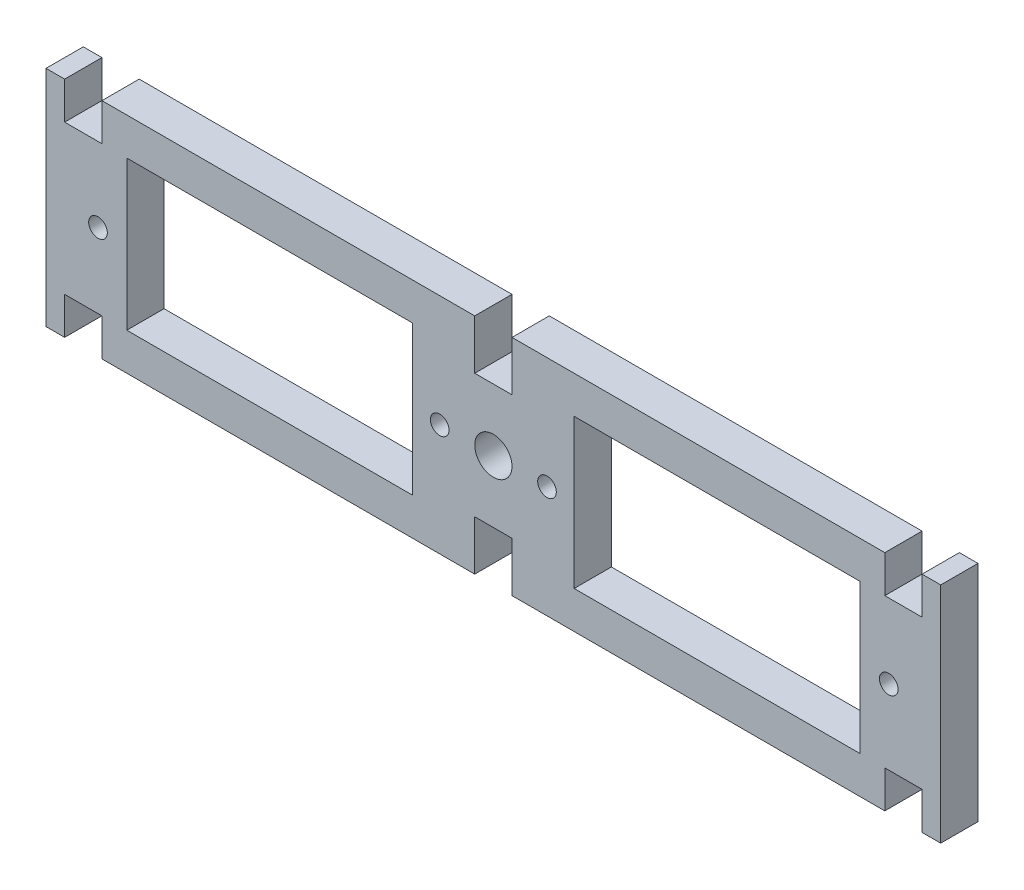
SolidWorks part; units mm, degrees
ref_plane "前视基准面" through (0, 0, 0) normal (0, 0, 1) x (1, 0, 0)
ref_plane "上视基准面" through (0, 0, 0) normal (0, 1, 0) x (1, 0, 0)
ref_plane "右视基准面" through (0, 0, 0) normal (1, 0, 0) x (0, 0, -1)
other "Configuration Table"
sketch "草图1" plane through (0, 0, 0) normal (0, 0, 1) x (1, 0, 0)
  line L0 (0, 0) -> (0, -18)
  line L1 (0, -18) -> (1.5, -18)
  line L2 (1.5, -18) -> (1.5, -15)
  line L3 (1.5, -15) -> (4.5, -15)
  line L4 (4.5, -15) -> (4.5, -18)
  line L5 (4.5, -18) -> (34.5, -18)
  line L6 (34.5, -18) -> (34.5, -14)
  line L7 (34.5, -14) -> (37.5, -14)
  line L8 (0, 0) -> (1.5, 0)
  line L9 (1.5, 0) -> (1.5, -3)
  line L10 (1.5, -3) -> (4.5, -3)
  line L11 (4.5, -3) -> (4.5, 0)
  line L12 (4.5, 0) -> (34.5, 0)
  line L13 (34.5, 0) -> (34.5, -4)
  line L14 (34.5, -4) -> (37.5, -4)
  line L15 (36, 6.2675) -> (36, -27.0405) construction
  line L16 (29.5, -9) -> (29.5, -15)
  line L17 (42.5, -24.4938) -> (29.5, -24.4938) construction
  line L18 (29.5, -15) -> (6.5, -15)
  line L19 (0, -9) -> (7.1186, -9) construction
  line L20 (6.5, -15) -> (6.5, -3)
  line L21 (6.5, -3) -> (29.5, -3)
  line L22 (29.5, -3) -> (29.5, -9)
  line L23 (40.4, -6.082) -> (31.6, -6.082) construction
  line L24 (42.5, -3) -> (42.5, -9)
  line L25 (65.5, -3) -> (42.5, -3)
  line L26 (65.5, -15) -> (65.5, -3)
  line L27 (42.5, -15) -> (65.5, -15)
  line L28 (42.5, -9) -> (42.5, -15)
  line L29 (37.5, 0) -> (37.5, -4)
  line L30 (67.5, 0) -> (37.5, 0)
  line L31 (67.5, -3) -> (67.5, 0)
  line L32 (70.5, -3) -> (67.5, -3)
  line L33 (70.5, 0) -> (70.5, -3)
  line L34 (72, 0) -> (70.5, 0)
  line L35 (37.5, -18) -> (37.5, -14)
  line L36 (67.5, -18) -> (37.5, -18)
  line L37 (67.5, -15) -> (67.5, -18)
  line L38 (70.5, -15) -> (67.5, -15)
  line L39 (70.5, -18) -> (70.5, -15)
  line L40 (72, -18) -> (70.5, -18)
  line L41 (72, 0) -> (72, -18)
  circle A0 centre (36, -9) radius 1.4997
  circle A1 centre (31.6838, -9) radius 0.75
  circle A2 centre (4.1838, -9) radius 0.75
  circle A3 centre (67.8162, -9) radius 0.75
  circle A4 centre (40.3162, -9) radius 0.75
  point P38 (36, -6.082)
  point P39 (36, -24.4938)
  point P48 (36, -4)
  point P55 (36, -14)
  dimension "D12" = 12
  dimension "D13" = 1.4997
  dimension "D15" = 1.5
  dimension "D16" = 1.5
  dimension "D1" = 18
  dimension "D2" = 1.5
  dimension "D3" = 3
  dimension "D4" = 3
  dimension "D5" = 30
  dimension "D6" = 4
  dimension "D7" = 1.5
  dimension "D8" = 3
  dimension "D9" = 4
  dimension "D10" = 6.5
  dimension "D11" = 23
  dimension "D14" = 4.4
  dimension "D17" = 27.5
extrude "凸台-拉伸1" add sketch "草图1" along normal blind 3
